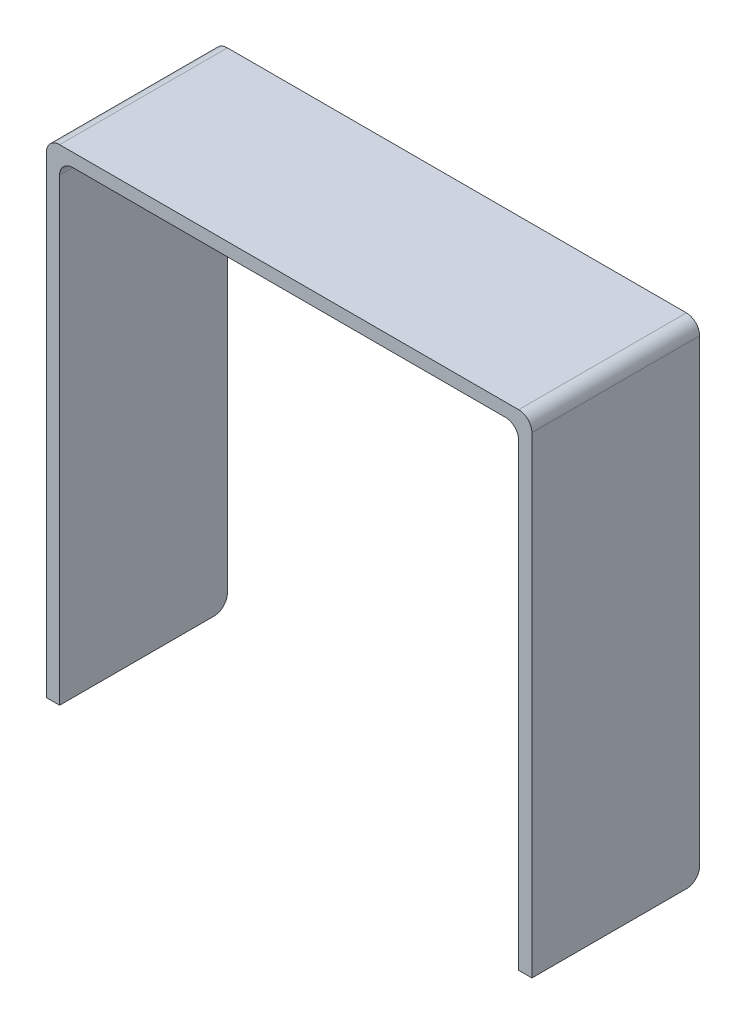
SolidWorks part; units mm, degrees
ref_plane "前视基准面" through (0, 0, 0) normal (0, 0, 1) x (1, 0, 0)
ref_plane "上视基准面" through (0, 0, 0) normal (0, 1, 0) x (1, 0, 0)
ref_plane "右视基准面" through (0, 0, 0) normal (1, 0, 0) x (0, 0, -1)
sketch "草图1" plane through (0, 0, 0) normal (0, 1, 0) x (1, 0, 0)
  line L1 (-55, 19) -> (55, 19)
  line L2 (-55, 19) -> (-55, -19)
  line L3 (-55, -19) -> (55, -19)
  line L4 (55, 19) -> (55, -19)
  line L5 (-55, 19) -> (55, -19) construction
  line L6 (-55, -19) -> (55, 19) construction
  line L15 (-55, 19) -> (-52, 19)
  line L16 (-55, 19) -> (-55, -19)
  line L17 (-55, -19) -> (-52, -19)
  line L18 (-52, 19) -> (-52, -19)
  line L23 (55, 19) -> (52, 19)
  line L24 (55, 19) -> (55, -19)
  line L25 (55, -19) -> (52, -19)
  line L26 (52, 19) -> (52, -19)
  point P0 (0, 0)
extrude "凸台-拉伸1" add sketch "草图1" along normal blind 3 contours L23 L26 L25 L24 | L15 L18 L17 L16 | L1 L2 L3 L4
sketch "草图4" plane through (0, 0, 0) normal (0, -1, 0) x (1, 0, 0)
  line L0 (55, 19) -> (-55, 19) construction
  line L1 (55, -19) -> (52, -19)
  line L2 (55, -19) -> (55, 19)
  line L3 (55, 19) -> (52, 19)
  line L4 (52, -19) -> (52, 19)
  line L6 (-55, -19) -> (-52, -19)
  line L7 (-55, -19) -> (-55, 19)
  line L8 (-55, 19) -> (-52, 19)
  line L9 (-52, -19) -> (-52, 19)
extrude "凸台-拉伸3" add sketch "草图4" along normal blind 107
fillet "圆角1" radius 3 2 edges at (-55, 3, 0) (55, 3, 0)
fillet "圆角2" radius 3 1 edges at (52, 0, 0)
fillet "圆角3" radius 3 1 edges at (-52, 0, 0)
fillet "圆角5" radius 3 2 edges at (-53.5, -107, -19) (53.5, -107, -19)
